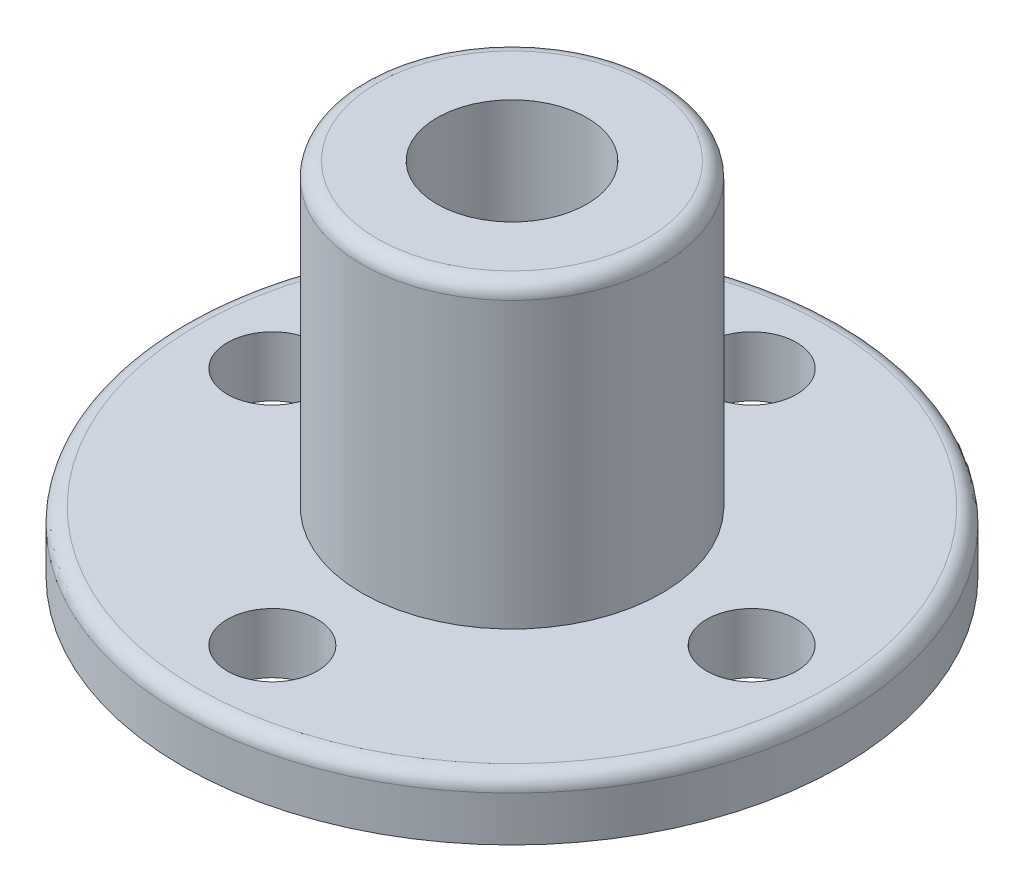
SolidWorks part; units mm, degrees
material "黄铜"
ref_plane "前视基准面" through (0, 0, 0) normal (0, 0, 1) x (1, 0, 0)
ref_plane "上视基准面" through (0, 0, 0) normal (0, 1, 0) x (1, 0, 0)
ref_plane "右视基准面" through (0, 0, 0) normal (1, 0, 0) x (0, 0, -1)
sketch "草图1" plane through (0, 0, 0) normal (0, 1, 0) x (1, 0, 0)
  circle A0 centre (0, 0) radius 11
  dimension "D1" = 22
extrude "凸台-拉伸1" add sketch "草图1" along normal blind 2
sketch "草图2" plane through (0, 2, 0) normal (0, 1, 0) x (1, 0, 0)
  circle A0 centre (0, 0) radius 5
  dimension "10" = 10
extrude "凸台-拉伸2" add sketch "草图2" along normal blind 10
sketch "草图3" plane through (0, 12, 0) normal (0, 1, 0) x (1, 0, 0)
  circle A0 centre (0, 0) radius 2.5
  dimension "D1" = 5
extrude "切除-拉伸1" cut sketch "草图3" against normal blind 10
sketch "草图4" plane through (0, 2, 0) normal (0, 1, 0) x (1, 0, 0)
  circle A0 centre (0, 0) radius 8
  dimension "D1" = 16
sketch "草图5" plane through (0, 2, 0) normal (0, 1, 0) x (1, 0, 0)
  circle A0 centre (0, 0) radius 8 construction
  point P0 (0, 8)
  point P4 (8, 0)
  point P6 (0, -8)
  point P8 (-8, 0)
hole_wizard "孔1" positions "草图5" profile "草图6" legacy end condition up to next
sketch "草图6" plane through (0, 2, -8) normal (1, 0, 0) x (0, 0, 1)
  line L0 (0, 0) -> (0, 2)
  line L1 (0, 2) -> (1.5, 2)
  line L2 (1.5, 2) -> (1.5, 0)
  line L3 (1.5, 0) -> (0, 0)
  line L4 (0, 110) -> (0, -10) construction
  dimension "直径" = 3
  dimension "深度" = 2
fillet "圆角1" radius 0.5 2 edges at (0, 12, 5) (0, 2, 11)
